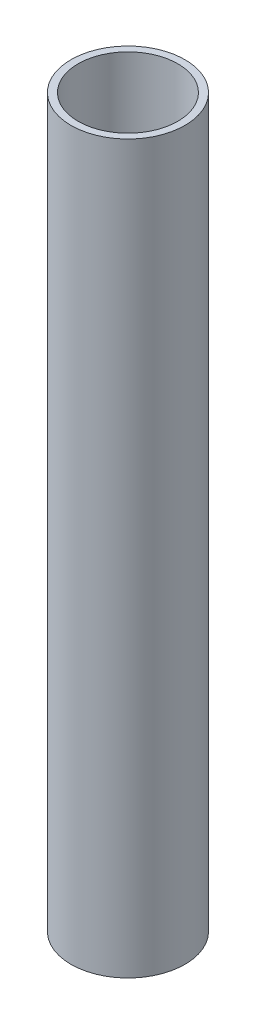
SolidWorks part; units mm, degrees
material "6061 Alloy"
ref_plane "Front Plane" through (0, 0, 0) normal (0, 0, 1) x (1, 0, 0)
ref_plane "Top Plane" through (0, 0, 0) normal (0, 1, 0) x (1, 0, 0)
ref_plane "Right Plane" through (0, 0, 0) normal (1, 0, 0) x (0, 0, -1)
sketch "Sketch1" plane through (0, 0, 0) normal (0, 1, 0) x (1, 0, 0)
  circle A0 centre (0, 0) radius 22.225
  circle A1 centre (0, 0) radius 25.4
  dimension "D1" = 50.8
  dimension "D2" = 3.175
extrude "Boss-Extrude1" add sketch "Sketch1" along normal blind 323.85
